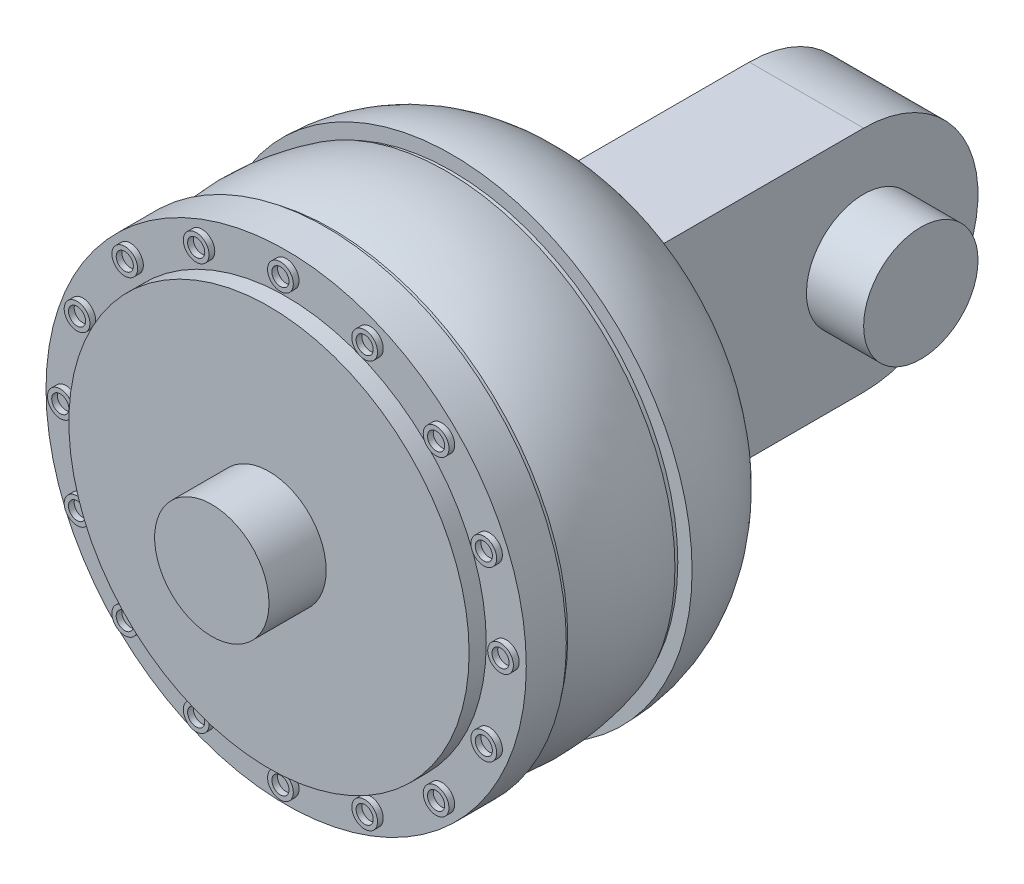
SolidWorks part; units mm, degrees
ref_plane "Front Plane" through (0, 0, 0) normal (0, 0, 1) x (1, 0, 0)
ref_plane "Top Plane" through (0, 0, 0) normal (0, 1, 0) x (1, 0, 0)
ref_plane "Right Plane" through (0, 0, 0) normal (1, 0, 0) x (0, 0, -1)
sketch "Sketch1" plane through (0, 0, 0) normal (0, 1, 0) x (1, 0, 0)
  line L0 (-32, 0) -> (0, 0)
  line L1 (0, 0) -> (0, -20)
  line L2 (0, -20) -> (-42, -20)
  arc A0 (-42, -20) -> (-32, 0) centre (-17, -20) cw
  dimension "D3" = 25
  dimension "D1" = 20
  dimension "D2" = 42
revolve "Revolve1" add sketch "Sketch1" angle 360 about L1
sketch "Sketch2" plane through (0, 0, 20) normal (0, 0, 1) x (1, 0, 0)
  circle A0 centre (0, 0) radius 39.5
  dimension "D1" = 79
extrude "Boss-Extrude1" add sketch "Sketch2" along normal blind 1
sketch "Sketch3" plane through (0, 0, 0) normal (0, 1, 0) x (1, 0, 0)
  line L0 (0, -21) -> (-40, -21)
  line L1 (-39.5, -21) -> (39.5, -21) construction
  line L2 (0, -21) -> (0, -41)
  line L3 (0, -41) -> (-40, -41)
  arc A0 (-40, -21) -> (-40, -41) centre (-4.377, -31) ccw
  dimension "D4" = 37
  dimension "D1" = 20
  dimension "D2" = 40
  dimension "D3" = 40
revolve "Revolve2" add sketch "Sketch3" angle 360 about L2
sketch "Sketch4" plane through (0, 0, 41) normal (0, 0, 1) x (1, 0, 0)
  circle A0 centre (0, 0) radius 41.25
  dimension "D1" = 82.5
extrude "Boss-Extrude2" add sketch "Sketch4" along normal blind 1
sketch "Sketch5" plane through (0, 0, 42) normal (0, 0, 1) x (1, 0, 0)
  circle A0 centre (0, 0) radius 42
  dimension "D1" = 84
extrude "Boss-Extrude3" add sketch "Sketch5" along normal blind 7
sketch "Sketch6" plane through (0, 0, 49) normal (0, 0, 1) x (1, 0, 0)
  circle A0 centre (0, 0) radius 35
  dimension "D1" = 70
extrude "Boss-Extrude4" add sketch "Sketch6" along normal blind 3
sketch "Sketch7" plane through (0, 0, 49) normal (0, 0, 1) x (1, 0, 0)
  line L0 (35, 0) -> (42, 0)
  circle A0 centre (0, 0) radius 35 construction
  circle A1 centre (0, 0) radius 35 construction
  circle A2 centre (0, 0) radius 42 construction
  circle A3 centre (38.5, 0) radius 2.25
  circle A4 centre (38.5, 0) radius 1.5
  dimension "D1" = 4.5
  dimension "D2" = 3
extrude "Boss-Extrude5" add sketch "Sketch7" along normal blind 1 contours A4 L0 A3 | A4 L0 A3
pattern_circular "CirPattern1" count 16 over 360 about axis through (0, 0, 0) along (0, 0, 1) of "Boss-Extrude5"
sketch "Sketch8" plane through (0, 0, 0) normal (0, 0, -1) x (-1, 0, 0)
  line L1 (-10, 20) -> (10, 20)
  line L2 (-10, 20) -> (-10, -20)
  line L3 (-10, -20) -> (10, -20)
  line L4 (10, 20) -> (10, -20)
  line L5 (-10, 20) -> (10, -20) construction
  line L6 (-10, -20) -> (10, 20) construction
  point P0 (0, 0)
  dimension "D1" = 40
  dimension "D2" = 20
extrude "Boss-Extrude6" add sketch "Sketch8" along normal blind 42
sketch "Sketch9" plane through (-10, 0, 0) normal (-1, 0, 0) x (0, 0, 1)
  line L0 (-42, -20) -> (-42, 20) construction
  circle A0 centre (-42, 0) radius 20
extrude "Boss-Extrude7" add sketch "Sketch9" against normal up to surface (20 mm away) up to face at (10, 0, -21)
sketch "Sketch11" plane through (0, 0, 52) normal (0, 0, 1) x (1, 0, 0)
  circle A0 centre (0, 0) radius 10
  dimension "D1" = 20
extrude "Boss-Extrude9" add sketch "Sketch11" along normal blind 10
sketch "Sketch12" plane through (10, 0, 0) normal (1, 0, 0) x (0, 0, -1)
  circle A0 centre (42, 0) radius 10
  dimension "D1" = 20
extrude "Boss-Extrude10" add sketch "Sketch12" along normal blind 10
ref_plane "Plane1" through (0, 0, 0) normal (1, 0, 0) x (0, 0, -1)
sketch "Sketch13" plane through (0, 0, 0) normal (1, 0, 0) x (0, 0, -1)
  point P0 (42, 0)
